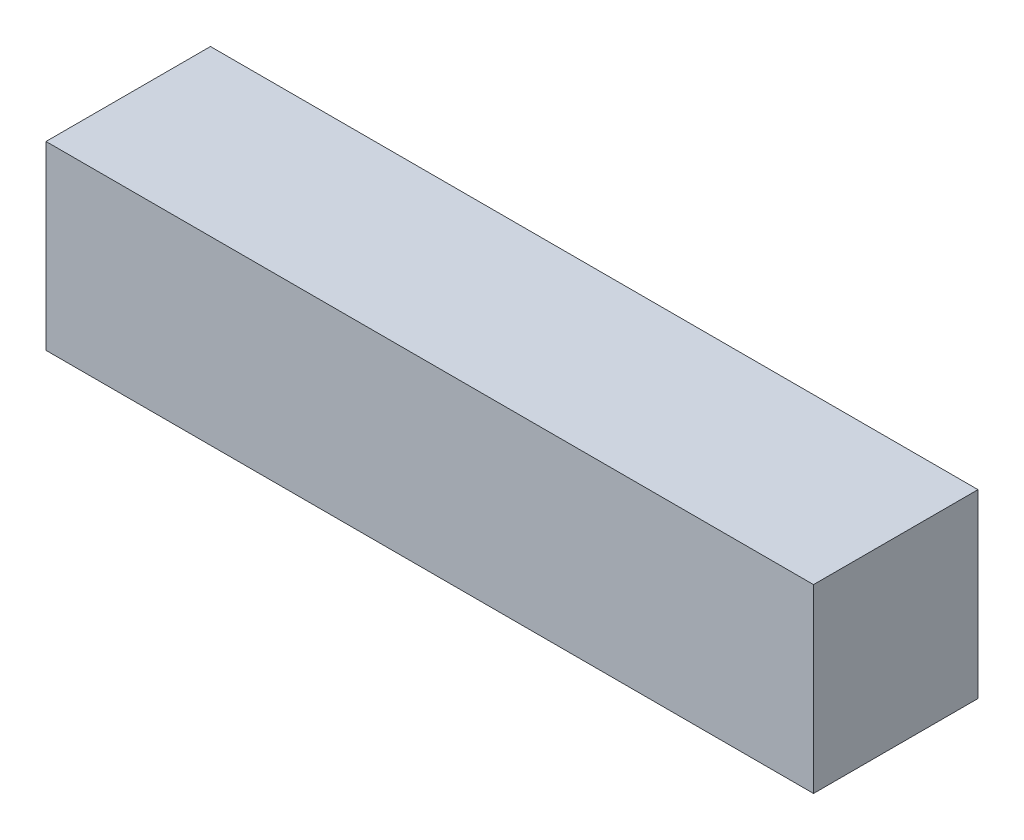
SolidWorks part; units mm, degrees
ref_plane "Front Plane" through (0, 0, 0) normal (0, 0, 1) x (1, 0, 0)
ref_plane "Top Plane" through (0, 0, 0) normal (0, 1, 0) x (1, 0, 0)
ref_plane "Right Plane" through (0, 0, 0) normal (1, 0, 0) x (0, 0, -1)
sketch "Sketch1" plane through (0, 0, 0) normal (0, 0, 1) x (1, 0, 0)
  line L0 (0, 0) -> (101.6, 0) construction
  line L1 (55, 0) -> (-55, 0) construction
  line L2 (0, 0) -> (0, -80.01) construction
  line L3 (0, -55) -> (0, 55) construction
  line L5 (0, 0) -> (88.9, 0)
  line L6 (0, 0) -> (0, -20.955)
  line L7 (0, -20.955) -> (88.9, -20.955)
  line L8 (88.9, 0) -> (88.9, -20.955)
  arc A0 (0, -80.01) -> (101.6, 0) centre (-12.2194, 40.0196) ccw construction
  dimension "D3" = 120.65
  dimension "D1" = 80.01
  dimension "D2" = 101.6
  dimension "D4" = 88.9
  dimension "D5" = 20.955
extrude "Boss-Extrude1" add sketch "Sketch1" along normal blind 19.05
